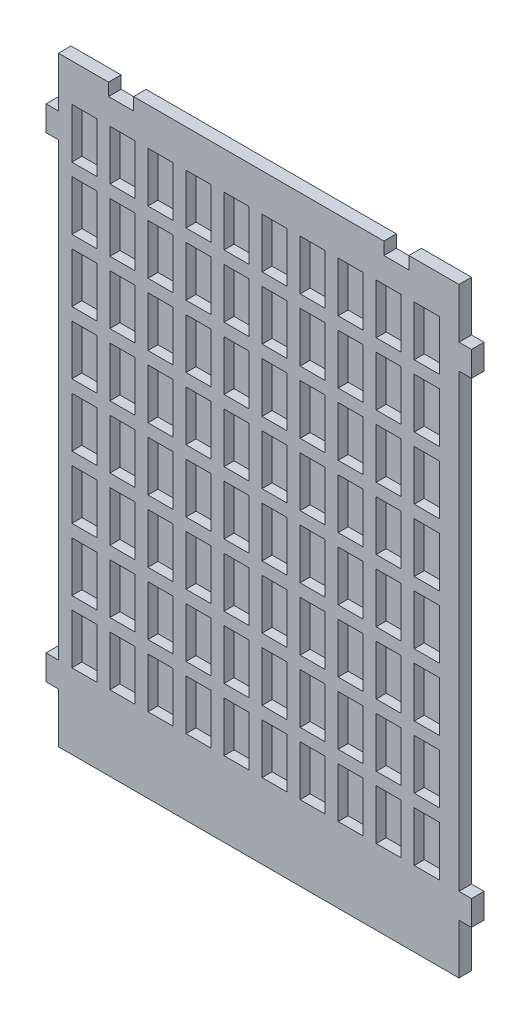
SolidWorks part; units mm, degrees
ref_plane "Front Plane" through (0, 0, 0) normal (0, 0, 1) x (1, 0, 0)
ref_plane "Top Plane" through (0, 0, 0) normal (0, 1, 0) x (1, 0, 0)
ref_plane "Right Plane" through (0, 0, 0) normal (1, 0, 0) x (0, 0, -1)
sketch "Sketch1" plane through (0, 0, 0) normal (0, 0, 1) x (1, 0, 0)
  line L0 (19.05, 0) -> (82.55, 0)
  line L1 (0, 0) -> (12.7, 0)
  line L2 (0, 0) -> (0, -12.7)
  line L3 (0, -152.4) -> (12.7, -152.4)
  line L4 (101.6, -19.05) -> (101.6, -133.35)
  line L5 (88.9, 0) -> (101.6, 0)
  line L6 (12.7, 0) -> (12.7, -3.175)
  line L7 (12.7, -3.175) -> (19.05, -3.175)
  line L8 (19.05, 0) -> (19.05, -3.175)
  line L9 (0, -19.05) -> (0, -133.35)
  line L10 (82.55, 0) -> (82.55, -3.175)
  line L11 (82.55, -3.175) -> (88.9, -3.175)
  line L12 (88.9, 0) -> (88.9, -3.175)
  line L13 (101.6, -12.7) -> (104.775, -12.7)
  line L14 (101.6, -139.7) -> (101.6, -152.4)
  line L15 (101.6, -19.05) -> (104.775, -19.05)
  line L16 (104.775, -12.7) -> (104.775, -19.05)
  line L17 (101.6, -133.35) -> (104.775, -133.35)
  line L18 (88.9, -152.4) -> (101.6, -152.4)
  line L19 (101.6, -139.7) -> (104.775, -139.7)
  line L20 (104.775, -133.35) -> (104.775, -139.7)
  line L21 (12.7, -152.4) -> (88.9, -152.4)
  line L25 (0, -139.7) -> (0, -152.4)
  line L29 (0, -139.7) -> (-3.175, -139.7)
  line L30 (101.6, 0) -> (101.6, -12.7)
  line L31 (0, -133.35) -> (-3.175, -133.35)
  line L32 (-3.175, -139.7) -> (-3.175, -133.35)
  line L33 (0, -19.05) -> (-3.175, -19.05)
  line L35 (0, -12.7) -> (-3.175, -12.7)
  line L36 (-3.175, -19.05) -> (-3.175, -12.7)
  dimension "D1" = 101.6
  dimension "D2" = 152.4
  dimension "D3" = 12.7
  dimension "D4" = 6.35
  dimension "D5" = 3.175
  dimension "D6" = 6.35
  dimension "D7" = 3.175
  dimension "D8" = 12.7
  dimension "D9" = 12.7
  dimension "D10" = 6.35
  dimension "D11" = 3.175
  dimension "D12" = 3.175
  dimension "D13" = 6.35
  dimension "D14" = 12.7
  dimension "D15" = 101.6
  dimension "D21" = 3.175
  dimension "D22" = 6.35
  dimension "D23" = 12.7
  dimension "D24" = 12.7
  dimension "D25" = 6.35
  dimension "D26" = 3.175
  dimension "D27" = 3.175
extrude "Boss-Extrude1" add sketch "Sketch1" along normal blind 3.175
sketch "Sketch2" plane through (0, 0, 3.175) normal (0, 0, 1) x (1, 0, 0)
  line L0 (12.7, -3.175) -> (19.05, -3.175) construction
  line L1 (3.3844, -9.525) -> (9.7344, -9.525)
  line L2 (3.3844, -9.525) -> (3.3844, -22.225)
  line L3 (3.3844, -22.225) -> (9.7344, -22.225)
  line L4 (9.7344, -9.525) -> (9.7344, -22.225)
  line L5 (3.3844, -9.525) -> (9.7344, -22.225) construction
  line L6 (3.3844, -22.225) -> (9.7344, -9.525) construction
  line L7 (0, -19.05) -> (0, -133.35) construction
  point P0 (6.5594, -15.875)
  dimension "D1" = 6.35
  dimension "D2" = 3.3844
  dimension "D3" = 12.7
  dimension "D4" = 6.35
extrude "Cut-Extrude1" cut sketch "Sketch2" against normal blind 2.54
pattern_linear "LPattern1" count 10 spacing 9.652 along (1, 0, 0) count 8 spacing 15.875 along (0, -1, 0) of "Cut-Extrude1"
